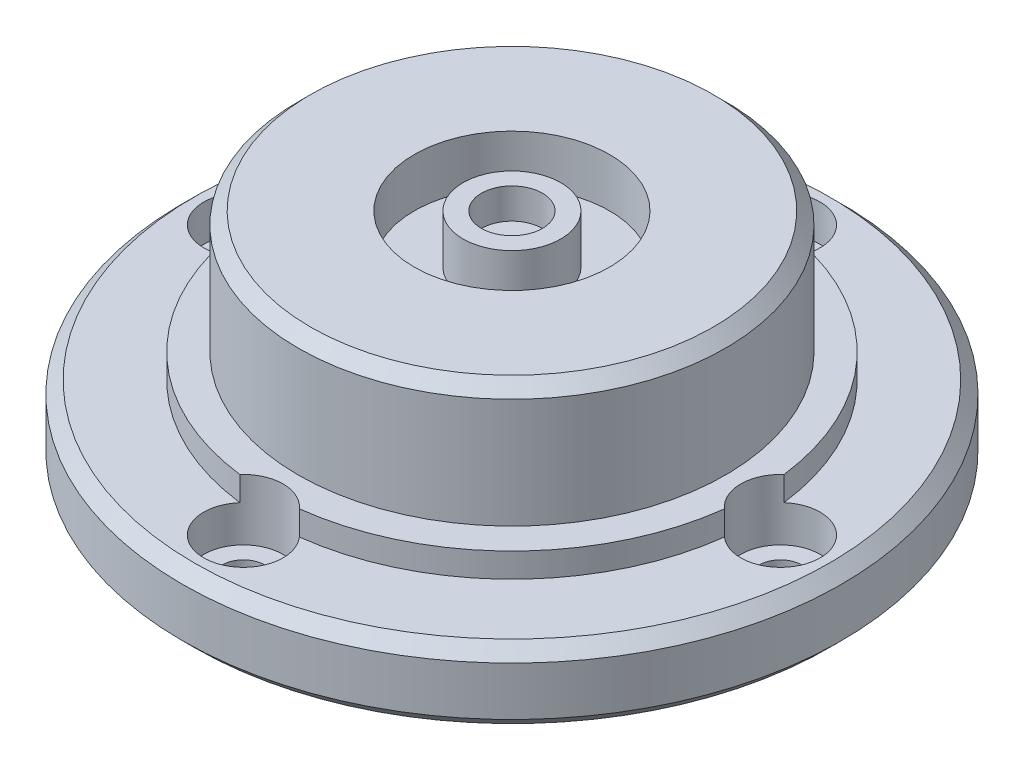
SolidWorks part; units mm, degrees
ref_plane "Front" through (0, 0, 0) normal (0, 0, 1) x (1, 0, 0)
ref_plane "Top" through (0, 0, 0) normal (0, 1, 0) x (1, 0, 0)
ref_plane "Right" through (0, 0, 0) normal (1, 0, 0) x (0, 0, -1)
sketch "Эскиз2" plane through (0, 0, 0) normal (0, 1, 0) x (1, 0, 0)
  circle A0 centre (0, 0) radius 27
  dimension "D1" = 54
extrude "Бобышка-Вытянуть1" add sketch "Эскиз2" along normal blind 18
sketch "Эскиз5" plane through (0, 0, 0) normal (0, 1, 0) x (1, 0, 0)
  circle A0 centre (0, 0) radius 14.1
  dimension "D1" = 28.2
extrude "Вырез-Вытянуть1" cut sketch "Эскиз5" along normal blind 5
sketch "Эскиз6" plane through (0, 0, 0) normal (0, 1, 0) x (1, 0, 0)
  circle A0 centre (0, 0) radius 20
  circle A2 centre (0, 0) radius 43.3851
  dimension "D1" = 40
extrude "Вырез-Вытянуть2" cut sketch "Эскиз6" along normal through all from offset 6
sketch "Эскиз7" plane through (0, 0, 0) normal (0, 1, 0) x (1, 0, 0)
  circle A0 centre (0, 0) radius 17.5
  circle A1 centre (0, 0) radius 38.1712
  dimension "D1" = 35
extrude "Вырез-Вытянуть3" cut sketch "Эскиз7" along normal through all from offset 8
sketch "Эскиз8" plane through (0, 0, 0) normal (0, 1, 0) x (1, 0, 0)
  circle A0 centre (0, 0) radius 22 construction
  circle A1 centre (0, 22) radius 1.75
  circle A2 centre (22, 0) radius 1.75
  circle A3 centre (0, -22) radius 1.75
  circle A4 centre (-22, 0) radius 1.75
  point P14 (0, 0)
  dimension "D1" = 4
  dimension "D2" = 44
extrude "Вырез-Вытянуть4" cut sketch "Эскиз8" along normal through all
sketch "Эскиз9" plane through (0, 0, 0) normal (0, 1, 0) x (1, 0, 0)
  circle A0 centre (0, 0) radius 22 construction
  circle A1 centre (0, 22) radius 3.25
  circle A2 centre (22, 0) radius 3.25
  circle A3 centre (0, -22) radius 3.25
  circle A4 centre (-22, 0) radius 3.25
  point P14 (0, 0)
  dimension "D1" = 4
  dimension "D2" = 44
extrude "Вырез-Вытянуть5" cut sketch "Эскиз9" along normal through all from offset 3
chamfer "Chamfer1" distance 1 angle 45 1 edges at (0, 0, 14.1)
chamfer "Chamfer2" distance 1 angle 45 1 edges at (0, 18, 17.5)
chamfer "Chamfer3" distance 1 angle 45 1 edges at (0, 0, 27)
chamfer "Chamfer4" distance 1 angle 45 1 edges at (0, 6, 27)
sketch "Эскиз10" plane through (0, 18, 0) normal (0, 1, 0) x (1, 0, 0)
  circle A0 centre (0, 0) radius 2.5
extrude "Вырез-Вытянуть6" cut sketch "Эскиз10" against normal blind 2.5
sketch "Эскиз11" plane through (0, 18, 0) normal (0, 1, 0) x (1, 0, 0)
  circle A0 centre (0, 0) radius 6 construction
  circle A1 centre (0, 0) radius 4
  circle A2 centre (0, 0) radius 8
  dimension "D1" = 16
  dimension "D2" = 8
extrude "Вырез-Вытянуть7" cut sketch "Эскиз11" against normal blind 4
